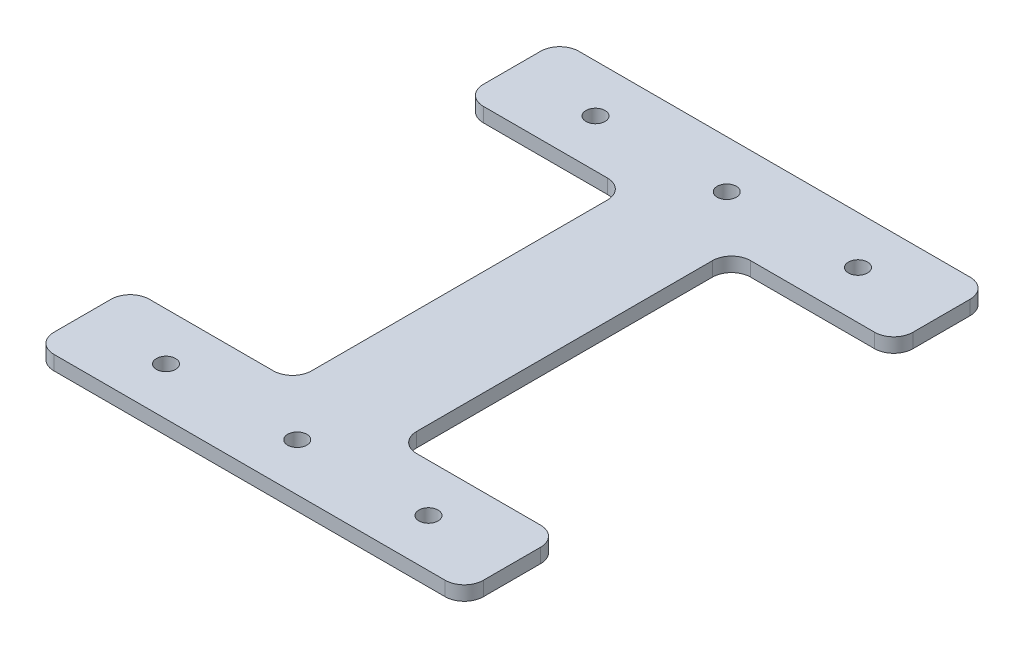
SolidWorks part; units mm, degrees
material "Thornel Mat VMA"
ref_plane "前视基准面" through (0, 0, 0) normal (0, 0, 1) x (1, 0, 0)
ref_plane "上视基准面" through (0, 0, 0) normal (0, 1, 0) x (1, 0, 0)
ref_plane "右视基准面" through (0, 0, 0) normal (1, 0, 0) x (0, 0, -1)
other "Configuration Table"
sketch "草图1" plane through (0, 0, 0) normal (0, 1, 0) x (1, 0, 0)
  line L0 (-22.9767, 0) -> (21.4576, 0) construction
  line L1 (-11, 35) -> (11, 35)
  line L2 (-11, 35) -> (-11, -35)
  line L3 (-11, -35) -> (11, -35)
  line L4 (11, 35) -> (11, -35)
  line L5 (-11, 35) -> (11, -35) construction
  line L6 (-11, -35) -> (11, 35) construction
  line L7 (-45, 55) -> (45, 55)
  line L8 (-45, 55) -> (-45, 35)
  line L9 (-45, 35) -> (45, 35)
  line L10 (45, 55) -> (45, 35)
  line L11 (-45, 55) -> (45, 35) construction
  line L12 (-45, 35) -> (45, 55) construction
  line L13 (-45, -35) -> (45, -35)
  line L14 (45, -55) -> (45, -35)
  line L15 (-45, -55) -> (45, -55)
  line L16 (-45, -55) -> (-45, -35)
  line L17 (0, 45) -> (-27.5, 45) construction
  line L18 (0, 17.1447) -> (0, -15.2975) construction
  circle A0 centre (0, 45) radius 2
  circle A1 centre (-27.5, 45) radius 2
  circle A2 centre (27.5, 45) radius 2
  circle A3 centre (27.5, -45) radius 2
  circle A4 centre (0, -45) radius 2
  circle A5 centre (-27.5, -45) radius 2
  point P0 (0, 0)
  point P5 (0, 45)
  point P31 (0, 0)
  point P32 (0, 0)
  point P33 (0, 0)
  point P34 (0, 0)
  dimension "D5" = 4
  dimension "D6" = 27.5
  dimension "D1" = 20
  dimension "D2" = 90
  dimension "D3" = 70
  dimension "D4" = 22
extrude "凸台-拉伸1" add sketch "草图1" along normal blind 3 contours L4 L1 L2 L3 | L10 L7 L8 L9 L1 A0 A1 A2 | L16 L15 L14 L13 L3 A4 A3 A5
fillet "圆角1" radius 4 12 edges at (11, 1.5, 35) (45, 1.5, 35) (45, 1.5, 55) (-45, 1.5, 55) (-45, 1.5, 35) (-11, 1.5, 35) (-11, 1.5, -35) (-45, 1.5, -35) (-45, 1.5, -55) (45, 1.5, -55) (45, 1.5, -35) (11, 1.5, -35)
